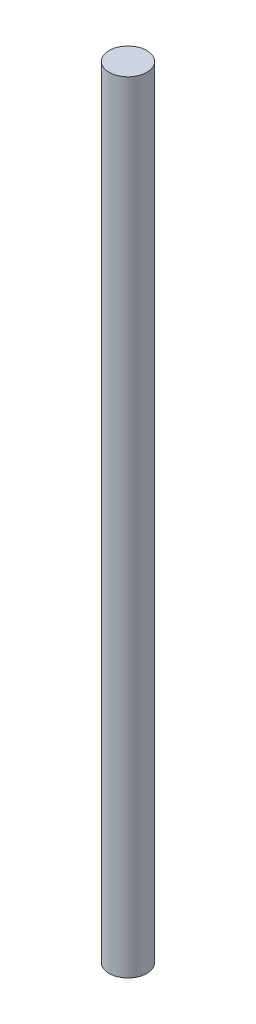
SolidWorks part; units mm, degrees
ref_plane "前视基准面" through (0, 0, 0) normal (0, 0, 1) x (1, 0, 0)
ref_plane "上视基准面" through (0, 0, 0) normal (0, 1, 0) x (1, 0, 0)
ref_plane "右视基准面" through (0, 0, 0) normal (1, 0, 0) x (0, 0, -1)
other "Configuration Table"
sketch "草图1" plane through (0, 0, 0) normal (0, 1, 0) x (1, 0, 0)
  circle A0 centre (0, 0) radius 2.9
  dimension "D1" = 5.8
extrude "凸台-拉伸1" add sketch "草图1" along normal blind 120 contours A0
